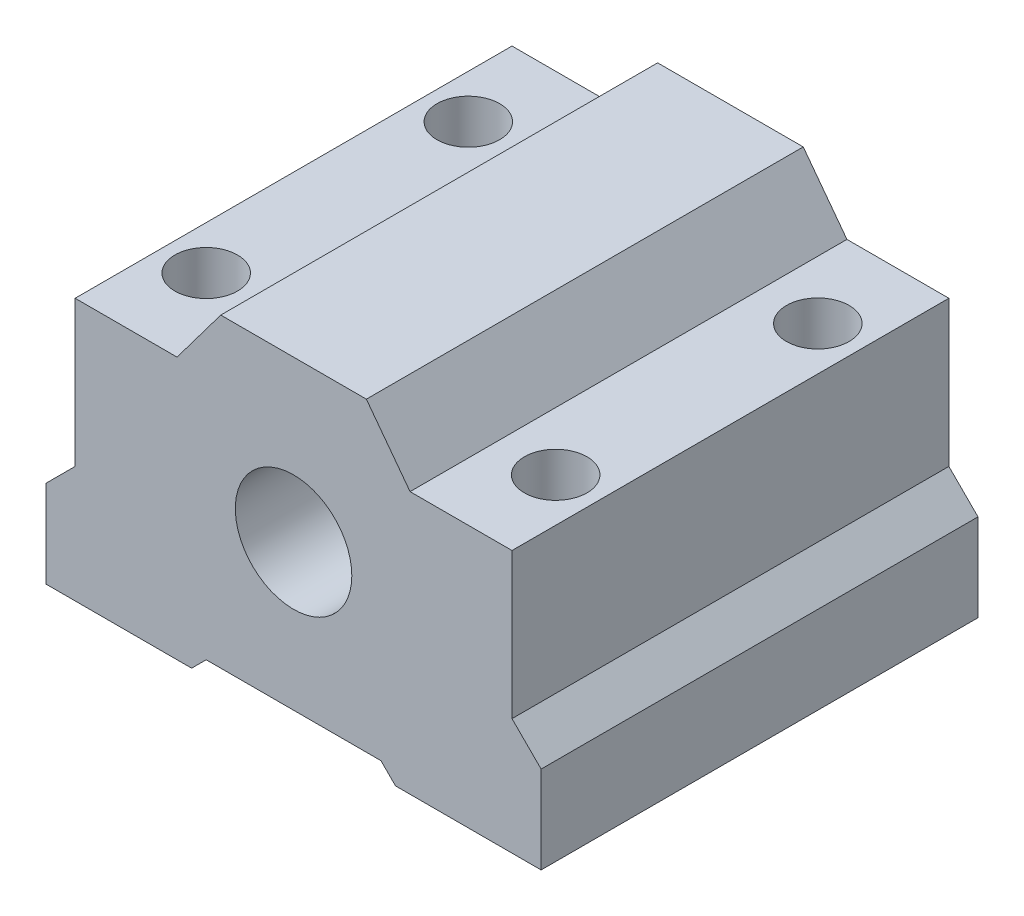
SolidWorks part; units mm, degrees
ref_plane "前视基准面" through (0, 0, 0) normal (0, 0, 1) x (1, 0, 0)
ref_plane "上视基准面" through (0, 0, 0) normal (0, 1, 0) x (1, 0, 0)
ref_plane "右视基准面" through (0, 0, 0) normal (1, 0, 0) x (0, 0, -1)
sketch "草图1" plane through (0, 0, 0) normal (0, 0, 1) x (1, 0, 0)
  line L0 (-5, 11) -> (5, 11)
  line L1 (5, 11) -> (8, 7)
  line L2 (8, 7) -> (15, 7)
  line L3 (15, 7) -> (15, -3)
  line L4 (15, -3) -> (17, -5)
  line L5 (17, -5) -> (17, -11)
  line L6 (17, -11) -> (7, -11)
  line L7 (7, -11) -> (6, -10)
  line L8 (6, -10) -> (-6, -10)
  line L9 (0, 16.7664) -> (0, -21.0672) construction
  line L10 (-7, -11) -> (-6, -10)
  line L11 (-17, -11) -> (-7, -11)
  line L12 (-17, -5) -> (-17, -11)
  line L13 (-15, -3) -> (-17, -5)
  line L14 (-15, 7) -> (-15, -3)
  line L15 (-8, 7) -> (-15, 7)
  line L16 (-5, 11) -> (-8, 7)
  circle A0 centre (0, 0) radius 4
  point P21 (0, -10)
  point P28 (0, 11)
  dimension "D2" = 8
  dimension "D1" = 17
  dimension "D3" = 22
  dimension "D4" = 11
  dimension "D5" = 6
  dimension "D6" = 8
  dimension "D7" = 18
  dimension "D8" = 7
  dimension "D9" = 6
  dimension "D10" = 5
  dimension "D11" = 7
  dimension "D12" = 1
  dimension "D13" = 2
extrude "凸台-拉伸1" add sketch "草图1" along normal blind 30
hole_wizard "M5 螺纹孔1" positions "草图2" profile "草图3" tap size "M5" standard "GB"
sketch "草图2" plane through (0, -11, 0) normal (0, -1, 0) x (-1, 0, 0)
  line L0 (-7, -30) -> (-17, -30) construction
  line L1 (17, -30) -> (7, -30) construction
  line L2 (-17, -30) -> (-17, 0) construction
  line L3 (17, -30) -> (17, 0) construction
  point P0 (12, -24)
  point P2 (12, -6)
  point P4 (-12, -24)
  point P6 (-12, -6)
  dimension "D1" = 18
  dimension "D2" = 18
  dimension "D3" = 6
  dimension "D4" = 6
  dimension "D5" = 5
  dimension "D6" = 5
  dimension "D7" = 5
  dimension "D8" = 5
sketch "草图3" plane through (-12, -11, 24) normal (1, 0, 0) x (0, 0, -1)
  line L0 (0, 0) -> (0, 19.2618)
  line L1 (0, 19.2618) -> (2.1, 18)
  line L2 (2.1, 18) -> (2.1, 0.425)
  line L3 (2.1, 0.425) -> (2.525, 0)
  line L5 (2.525, 0) -> (0, 0)
  line L6 (-2.1, 0.425) -> (-2.525, 0) construction
  line L10 (0, 19.2618) -> (-2.1, 18) construction
  line L11 (0, -6.35) -> (0, 107.95) construction
  dimension "螺纹孔钻头直径" = 4.2
  dimension "螺纹孔钻头深度" = 18
  dimension "近端锥形沉头孔直径" = 5.05
  dimension "近端锥形沉头孔角度" = 90
  dimension "导头角度" = 118
sketch "草图4" plane through (0, -11, 0) normal (0, -1, 0) x (1, 0, 0)
  circle A0 centre (-12, 24) radius 2.15
  circle A1 centre (12, 24) radius 2.15
  circle A2 centre (12, 6) radius 2.15
  circle A3 centre (-12, 6) radius 2.15
  dimension "D1" = 4.3
  dimension "D2" = 4.3
  dimension "D3" = 4.3
  dimension "D4" = 4.3
extrude "切除-拉伸1" cut sketch "草图4" against normal blind 30
